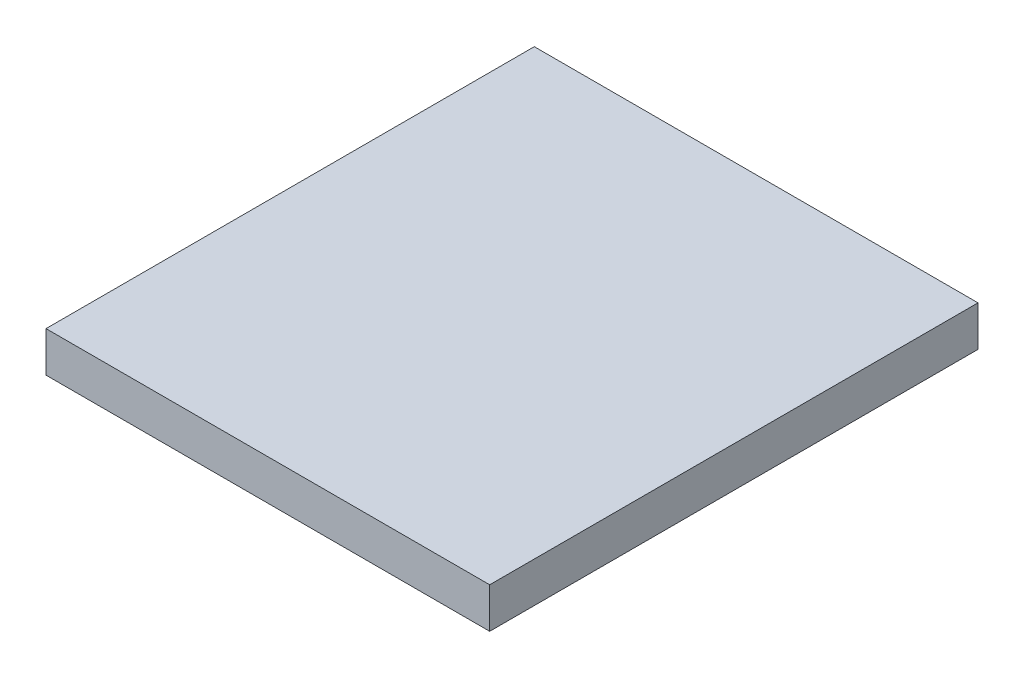
SolidWorks part; units mm, degrees
ref_plane "Front Plane" through (0, 0, 0) normal (0, 0, 1) x (1, 0, 0)
ref_plane "Top Plane" through (0, 0, 0) normal (0, 1, 0) x (1, 0, 0)
ref_plane "Right Plane" through (0, 0, 0) normal (1, 0, 0) x (0, 0, -1)
sketch "Sketch1" plane through (0, 0, 0) normal (0, 1, 0) x (1, 0, 0)
  line L1 (-54.4974, -59.9774) -> (54.4974, -59.9774)
  line L2 (-54.4974, -59.9774) -> (-54.4974, 59.9774)
  line L3 (-54.4974, 59.9774) -> (54.4974, 59.9774)
  line L4 (54.4974, -59.9774) -> (54.4974, 59.9774)
  line L5 (-54.4974, -59.9774) -> (54.4974, 59.9774) construction
  line L6 (-54.4974, 59.9774) -> (54.4974, -59.9774) construction
  point P0 (0, 0)
  dimension "D1" = 119.9547
  dimension "D2" = 108.9947
extrude "Boss-Extrude1" add sketch "Sketch1" along normal blind 9.906
